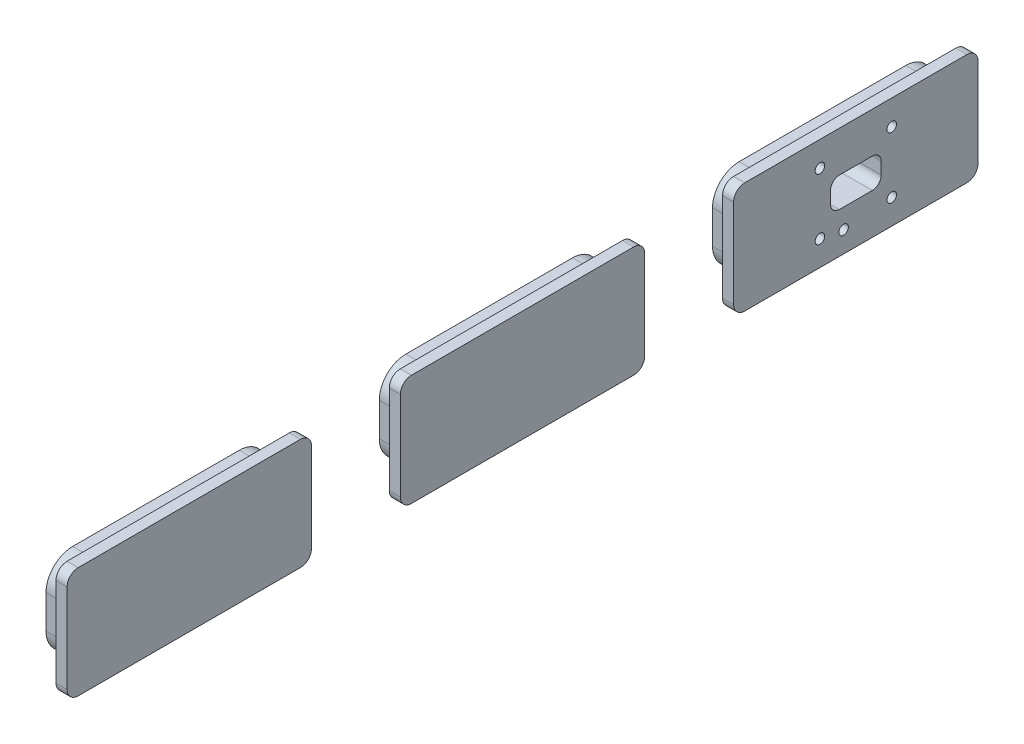
SolidWorks part; units mm, degrees
ref_plane "Front Plane" through (0, 0, 0) normal (0, 0, 1) x (1, 0, 0)
ref_plane "Top Plane" through (0, 0, 0) normal (0, 1, 0) x (1, 0, 0)
ref_plane "Right Plane" through (0, 0, 0) normal (1, 0, 0) x (0, 0, -1)
sketch "Sketch1" plane through (-330.42, 0, 0) normal (-1, 0, 0) x (0, 0, 1)
  line L43 (53.405, 35.5) -> (53.405, 50.5)
  line L44 (41.405, 62.5) -> (-33.595, 62.5)
  line L45 (-45.595, 50.5) -> (-45.595, 35.5)
  line L46 (-33.595, 23.5) -> (41.405, 23.5)
  line L47 (-96.595, 23.5) -> (-96.595, 62.5)
  line L48 (-195.595, 23.5) -> (-96.595, 23.5)
  line L49 (-195.595, 62.5) -> (-195.595, 23.5)
  line L50 (-96.595, 62.5) -> (-195.595, 62.5)
  line L51 (-96.595, 35.5) -> (-96.595, 50.5)
  line L52 (-183.595, 23.5) -> (-108.595, 23.5)
  line L53 (-195.595, 50.5) -> (-195.595, 35.5)
  line L54 (-108.595, 62.5) -> (-183.595, 62.5)
  line L55 (203.405, 35.5) -> (203.405, 50.5)
  line L56 (191.405, 62.5) -> (116.405, 62.5)
  line L57 (104.405, 50.5) -> (104.405, 35.5)
  line L58 (116.405, 23.5) -> (191.405, 23.5)
  line L59 (203.905, 63) -> (103.905, 63) construction
  arc A12 (-96.595, 50.5) -> (-108.595, 62.5) centre (-108.595, 50.5) ccw
  arc A13 (-96.595, 35.5) -> (-108.595, 23.5) centre (-108.595, 35.5) cw
  arc A14 (-195.595, 35.5) -> (-183.595, 23.5) centre (-183.595, 35.5) ccw
  arc A15 (-195.595, 50.5) -> (-183.595, 62.5) centre (-183.595, 50.5) cw
  arc A16 (53.405, 35.5) -> (41.405, 23.5) centre (41.405, 35.5) cw
  arc A17 (53.405, 50.5) -> (41.405, 62.5) centre (41.405, 50.5) ccw
  arc A18 (-45.595, 50.5) -> (-33.595, 62.5) centre (-33.595, 50.5) cw
  arc A19 (-45.595, 35.5) -> (-33.595, 23.5) centre (-33.595, 35.5) ccw
  arc A20 (203.405, 35.5) -> (191.405, 23.5) centre (191.405, 35.5) cw
  arc A21 (203.405, 50.5) -> (191.405, 62.5) centre (191.405, 50.5) ccw
  arc A22 (104.405, 50.5) -> (116.405, 62.5) centre (116.405, 50.5) cw
  arc A23 (104.405, 35.5) -> (116.405, 23.5) centre (116.405, 35.5) ccw
  point P14 (153.905, 62.5)
  point P45 (153.905, 63)
  dimension "D1" = 0.5
  dimension "D2" = 12
  dimension "D3" = 3
extrude "Boss-Extrude1" add sketch "Sketch1" against normal up to surface (10 mm away)
sketch "Sketch2" plane through (-320.42, 0, 0) normal (1, 0, 0) x (0, 0, -1)
  line L10 (51.095, 23) -> (51.095, 63)
  line L11 (46.095, 68) -> (-53.905, 68)
  line L12 (-58.905, 63) -> (-58.905, 23)
  line L13 (-53.905, 18) -> (46.095, 18)
  line L14 (201.095, 18) -> (201.095, 68)
  line L15 (91.095, 18) -> (201.095, 18)
  line L16 (91.095, 68) -> (91.095, 18)
  line L17 (201.095, 68) -> (91.095, 68)
  line L18 (201.095, 23) -> (201.095, 63)
  line L19 (96.095, 18) -> (196.095, 18)
  line L20 (91.095, 63) -> (91.095, 23)
  line L21 (196.095, 68) -> (96.095, 68)
  line L22 (-98.905, 23) -> (-98.905, 63)
  line L23 (-103.905, 68) -> (-203.905, 68)
  line L24 (-208.905, 63) -> (-208.905, 23)
  line L25 (-203.905, 18) -> (-103.905, 18)
  line L27 (-53.905, 63) -> (46.095, 63) construction
  arc A0 (201.095, 63) -> (196.095, 68) centre (196.095, 63) ccw
  arc A1 (201.095, 23) -> (196.095, 18) centre (196.095, 23) cw
  arc A2 (96.095, 18) -> (91.095, 23) centre (96.095, 23) cw
  arc A3 (91.095, 63) -> (96.095, 68) centre (96.095, 63) cw
  arc A4 (51.095, 23) -> (46.095, 18) centre (46.095, 23) cw
  arc A5 (51.095, 63) -> (46.095, 68) centre (46.095, 63) ccw
  arc A6 (-58.905, 63) -> (-53.905, 68) centre (-53.905, 63) cw
  arc A7 (-53.905, 18) -> (-58.905, 23) centre (-53.905, 23) cw
  arc A8 (-98.905, 23) -> (-103.905, 18) centre (-103.905, 23) cw
  arc A9 (-98.905, 63) -> (-103.905, 68) centre (-103.905, 63) ccw
  arc A10 (-208.905, 63) -> (-203.905, 68) centre (-203.905, 63) cw
  arc A11 (-203.905, 18) -> (-208.905, 23) centre (-203.905, 23) cw
  point P44 (-3.905, 63)
  point P45 (-3.905, 68)
  dimension "D2" = 5
  dimension "D1" = 5
  dimension "D3" = 3
extrude "Boss-Extrude2" add sketch "Sketch2" along normal blind 5
sketch "Sketch5" plane through (-330.42, 0, 0) normal (-1, 0, 0) x (0, 0, 1)
  line L0 (-162.245, 56.75) -> (-129.945, 56.75) construction
  line L1 (-168.795, 63.3) -> (-123.395, 63.3) construction
  line L2 (-168.795, 63.3) -> (-168.795, 22.7) construction
  line L3 (-168.795, 22.7) -> (-123.395, 22.7) construction
  line L4 (-123.395, 63.3) -> (-123.395, 22.7) construction
  line L5 (-162.245, 56.75) -> (-162.245, 29.25) construction
  line L6 (-100.095, 48.8) -> (-100.095, 37.2) construction
  line L7 (-108.595, 62.5) -> (-183.595, 62.5) construction
  line L9 (-153.495, 49.7) -> (-138.695, 49.7)
  line L10 (-157.495, 45.7) -> (-157.495, 40.3)
  line L11 (-153.495, 36.3) -> (-138.695, 36.3)
  line L12 (-134.695, 45.7) -> (-134.695, 40.3)
  circle A0 centre (-162.245, 56.75) radius 2.15
  circle A1 centre (-129.945, 56.75) radius 2.15
  circle A2 centre (-129.945, 29.25) radius 2.15
  circle A3 centre (-162.245, 29.25) radius 2.15
  circle A4 centre (-140.595, 27.45) radius 2.15
  arc A5 (-157.495, 40.3) -> (-153.495, 36.3) centre (-153.495, 40.3) ccw
  arc A6 (-138.695, 36.3) -> (-134.695, 40.3) centre (-138.695, 40.3) ccw
  arc A7 (-138.695, 49.7) -> (-134.695, 45.7) centre (-138.695, 45.7) cw
  arc A8 (-153.495, 49.7) -> (-157.495, 45.7) centre (-153.495, 45.7) ccw
  point P7 (-146.095, 56.75)
  point P8 (-146.095, 63.3)
  point P17 (-162.245, 43)
  point P18 (-168.795, 43)
  point P19 (-123.395, 43)
  point P22 (-100.095, 43)
  point P25 (-146.095, 62.5)
  point P30 (-146.095, 49.7)
  point P31 (-157.495, 43)
  point P34 (-134.695, 43)
  point P35 (-146.095, 36.3)
  point P38 (-157.495, 36.3)
  point P43 (-134.695, 49.7)
  point P46 (-157.495, 49.7)
  dimension "D1" = 4.3
  dimension "D8" = 15.55
  dimension "D12" = 4
  dimension "D2" = 2
  dimension "D4" = 32.3
  dimension "D5" = 27.5
  dimension "D6" = 45.4
  dimension "D7" = 40.6
  dimension "D9" = 5.5
  dimension "D10" = 22.8
  dimension "D11" = 13.4
  dimension "D3" = 2
extrude "Cut-Extrude3" cut sketch "Sketch5" against normal through all
sketch "Sketch6" plane through (-330.42, 0, 0) normal (-1, 0, 0) x (0, 0, 1)
  line L1 (-162.122, 56.9992) -> (-129.945, 56.9992)
  line L2 (-162.122, 56.9992) -> (-162.122, 29.25)
  line L3 (-162.122, 29.25) -> (-129.945, 29.25)
  line L4 (-129.945, 56.9992) -> (-129.945, 29.25)
